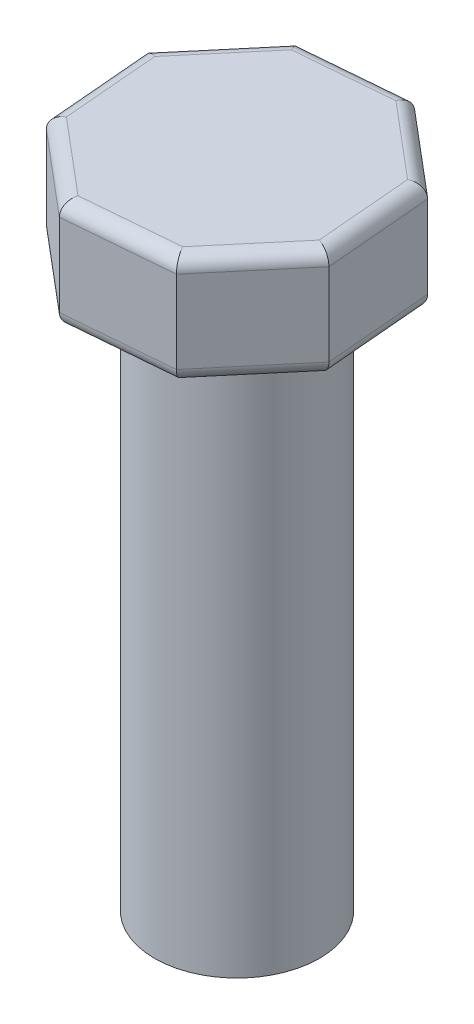
SolidWorks part; units mm, degrees
ref_plane "Front Plane" through (0, 0, 0) normal (0, 0, 1) x (1, 0, 0)
ref_plane "Top Plane" through (0, 0, 0) normal (0, 1, 0) x (1, 0, 0)
ref_plane "Right Plane" through (0, 0, 0) normal (1, 0, 0) x (0, 0, -1)
sketch "Sketch1" plane through (0, 0, 0) normal (0, 1, 0) x (1, 0, 0)
  line L1 (9.7993, -3.1157) -> (9.1323, 4.7261)
  line L2 (9.1323, 4.7261) -> (3.1157, 9.7993)
  line L3 (3.1157, 9.7993) -> (-4.7261, 9.1323)
  line L4 (-4.7261, 9.1323) -> (-9.7993, 3.1157)
  line L5 (-9.7993, 3.1157) -> (-9.1323, -4.7261)
  line L6 (-9.1323, -4.7261) -> (-3.1157, -9.7993)
  line L7 (-3.1157, -9.7993) -> (4.7261, -9.1323)
  line L8 (4.7261, -9.1323) -> (9.7993, -3.1157)
  circle A0 centre (0, 0) radius 9.5 construction
  dimension "D1" = 19
extrude "Boss-Extrude1" add sketch "Sketch1" along normal blind 8 contours L4 L5 L6 L7 L8 L1 L2 L3
sketch "Sketch2" plane through (0, 0, 0) normal (0, -1, 0) x (1, 0, 0)
  circle A0 centre (0, 0) radius 6
  dimension "D1" = 12
extrude "Boss-Extrude2" add sketch "Sketch2" along normal blind 40
fillet "Fillet1" radius 1 16 edges at (9.4658, 8, -0.8052) (6.124, 8, -7.2627) (-0.8052, 8, -9.4658) (-7.2627, 8, -6.124) (-9.4658, 8, 0.8052) (-6.124, 8, 7.2627) (0.8052, 8, 9.4658) (7.2627, 8, 6.124) (-9.4658, 0, 0.8052) (-6.124, 0, 7.2627) (-7.2627, 0, -6.124) (-0.8052, 0, -9.4658) (6.124, 0, -7.2627) (9.4658, 0, -0.8052) (7.2627, 0, 6.124) (0.8052, 0, 9.4658)
